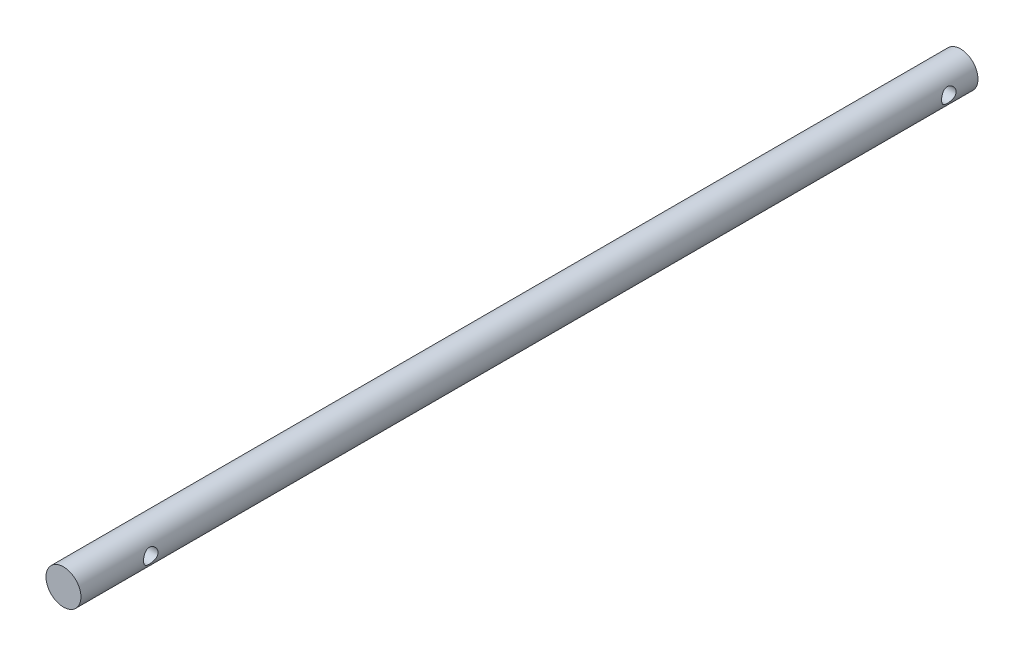
SolidWorks part; units mm, degrees
ref_plane "Front" through (0, 0, 0) normal (0, 0, 1) x (1, 0, 0)
ref_plane "Top" through (0, 0, 0) normal (0, 1, 0) x (1, 0, 0)
ref_plane "Right" through (0, 0, 0) normal (1, 0, 0) x (0, 0, -1)
sketch "Esquisse1" plane through (0, 0, 0) normal (0, 0, 1) x (1, 0, 0)
  circle A0 centre (0, 0) radius 2 construction
  circle A1 centre (0, 0) radius 3
  dimension "D1" = 6
  dimension "D2" = 4
extrude "Boss.-Extru.1" add sketch "Esquisse1" along normal blind 154
sketch "Esquisse2" plane through (0, 0, 0) normal (1, 0, 0) x (0, 0, -1)
  line L0 (0, -3) -> (0, 3) construction
  line L1 (0, 0) -> (-5, 0) construction
  line L2 (-154, 3) -> (-154, -3) construction
  circle A0 centre (-5, 0) radius 1.25
  circle A1 centre (-142, 0) radius 1.25
  point P8 (0, 0)
  dimension "D1" = 2.5
  dimension "D3" = 12
  dimension "D4" = 137
  dimension "D2" = 5
extrude "Enlèv. mat.-Extru.1" cut sketch "Esquisse2" against normal through all both and the other way through all
